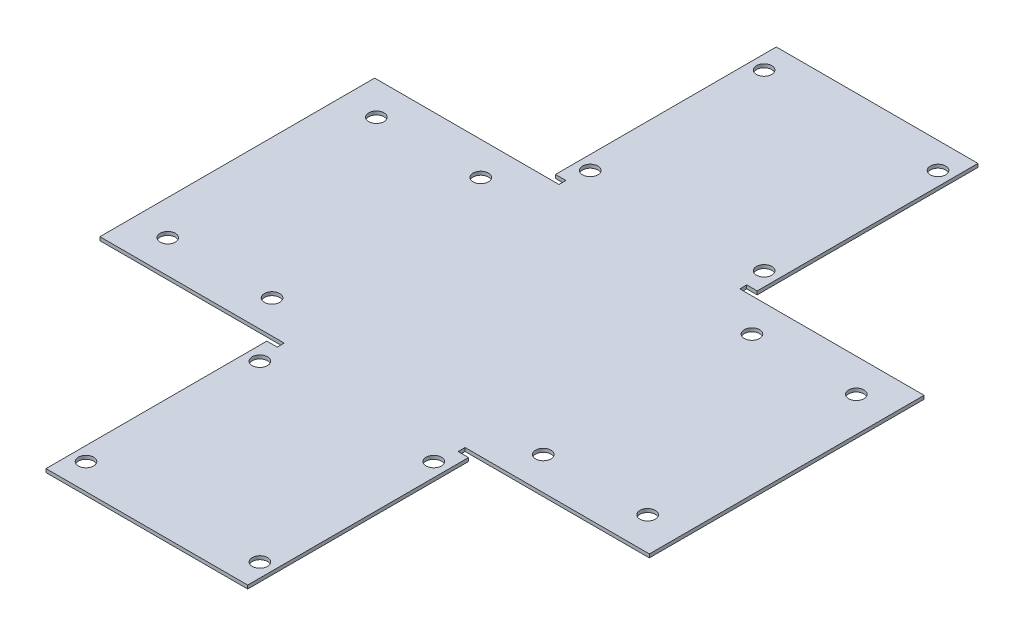
SolidWorks part; units mm, degrees
ref_plane "Front Plane" through (0, 0, 0) normal (0, 0, 1) x (1, 0, 0)
ref_plane "Top Plane" through (0, 0, 0) normal (0, 1, 0) x (1, 0, 0)
ref_plane "Right Plane" through (0, 0, 0) normal (1, 0, 0) x (0, 0, -1)
sketch "Sketch1" plane through (0, 0, 0) normal (0, 1, 0) x (1, 0, 0)
  line L0 (0, 39.5) -> (0, -39.5) construction
  line L1 (-25, 39.5) -> (-25, 0) construction
  line L2 (29, 72.5) -> (29, -72.5) construction
  line L7 (0, 39.5) -> (58, 39.5) construction
  line L8 (4, 97.5) -> (54, 97.5) construction
  line L9 (4, 97.5) -> (4, 47.5) construction
  line L10 (4, 47.5) -> (54, 47.5) construction
  line L11 (54, 97.5) -> (54, 47.5) construction
  line L12 (4, 97.5) -> (54, 47.5) construction
  line L13 (4, 47.5) -> (54, 97.5) construction
  line L19 (4, -47.5) -> (54, -47.5) construction
  line L20 (4, -47.5) -> (4, -97.5) construction
  line L22 (4, -97.5) -> (54, -97.5) construction
  line L23 (54, -47.5) -> (54, -97.5) construction
  line L26 (4, -47.5) -> (54, -97.5) construction
  line L27 (4, -97.5) -> (54, -47.5) construction
  line L28 (58, 39.5) -> (58, -39.5) construction
  line L29 (58, -39.5) -> (0, -39.5) construction
  line L30 (0, -39.5) -> (0, -41.5) construction
  line L31 (0, -41.5) -> (58, -41.5) construction
  line L32 (58, -41.5) -> (58, -39.5) construction
  line L33 (0, 39.5) -> (0, 41.5) construction
  line L36 (0, 41.5) -> (58, 41.5) construction
  line L37 (58, 41.5) -> (58, 39.5) construction
  line L40 (0, -39.5) -> (3, -39.5)
  line L41 (3, -39.5) -> (3, -41.5)
  line L42 (3, -41.5) -> (0, -41.5)
  line L43 (0, -41.5) -> (0, -105)
  line L44 (0, -105) -> (58, -105)
  line L45 (58, -105) -> (58, -41.5)
  line L46 (58, -41.5) -> (55, -41.5)
  line L47 (55, -41.5) -> (55, -39.5)
  line L50 (55, -39.5) -> (58, -39.5)
  line L51 (58, -39.5) -> (108, -39.5)
  line L54 (108, -39.5) -> (108, 39.5)
  line L55 (108, 39.5) -> (58, 39.5)
  line L56 (58, 39.5) -> (55, 39.5)
  line L77 (55, 39.5) -> (55, 41.5)
  line L78 (55, 41.5) -> (58, 41.5)
  line L79 (58, 41.5) -> (58, 105)
  line L80 (58, 105) -> (0, 105)
  line L81 (0, 105) -> (0, 41.5)
  line L82 (0, 41.5) -> (3, 41.5)
  line L83 (3, 41.5) -> (3, 39.5)
  line L84 (3, 39.5) -> (0, 39.5)
  line L85 (0, 39.5) -> (-50, 39.5)
  line L86 (-50, 39.5) -> (-50, -39.5)
  line L87 (-50, -39.5) -> (0, -39.5)
  line L88 (29, 0) -> (-25, 0) construction
  line L89 (-10, -30) -> (-40, -30) construction
  line L90 (-10, -30) -> (-10, 30) construction
  line L91 (-10, 30) -> (-40, 30) construction
  line L92 (-40, -30) -> (-40, 30) construction
  line L93 (-10, -30) -> (-40, 30) construction
  line L94 (-10, 30) -> (-40, -30) construction
  line L95 (98, -30) -> (68, -30) construction
  line L96 (98, -30) -> (98, 30) construction
  line L97 (98, 30) -> (68, 30) construction
  line L98 (68, -30) -> (68, 30) construction
  line L99 (98, -30) -> (68, 30) construction
  line L100 (98, 30) -> (68, -30) construction
  line L101 (-25, 0) -> (-50, 0) construction
  line L102 (83, 39.5) -> (83, 0) construction
  line L105 (108, 0) -> (83, 0) construction
  line L106 (83, 0) -> (29, 0) construction
  circle A55 centre (4, 97.5) radius 2.2
  circle A56 centre (54, 97.5) radius 2.2
  circle A57 centre (54, 47.5) radius 2.2
  circle A58 centre (4, 47.5) radius 2.2
  circle A59 centre (4, -47.5) radius 2.2
  circle A60 centre (54, -47.5) radius 2.2
  circle A61 centre (54, -97.5) radius 2.2
  circle A62 centre (4, -97.5) radius 2.2
  circle A63 centre (-40, 30) radius 2.2
  circle A64 centre (-10, 30) radius 2.2
  circle A65 centre (-40, -30) radius 2.2
  circle A66 centre (-10, -30) radius 2.2
  circle A67 centre (68, -30) radius 2.2
  circle A68 centre (98, -30) radius 2.2
  circle A69 centre (98, 30) radius 2.2
  circle A70 centre (68, 30) radius 2.2
  point P34 (-25, 0)
  point P50 (83, 0)
  dimension "D1" = 79
  dimension "D2" = 4.4
  dimension "D4" = 4
  dimension "D11" = 4.4
  dimension "D3" = 50
  dimension "D6" = 2
  dimension "D7" = 6
  dimension "D8" = 50
  dimension "D9" = 7.5
  dimension "D12" = 60
  dimension "D13" = 30
  dimension "D10" = 3
extrude "Boss-Extrude1" add sketch "Sketch1" along normal blind 1
